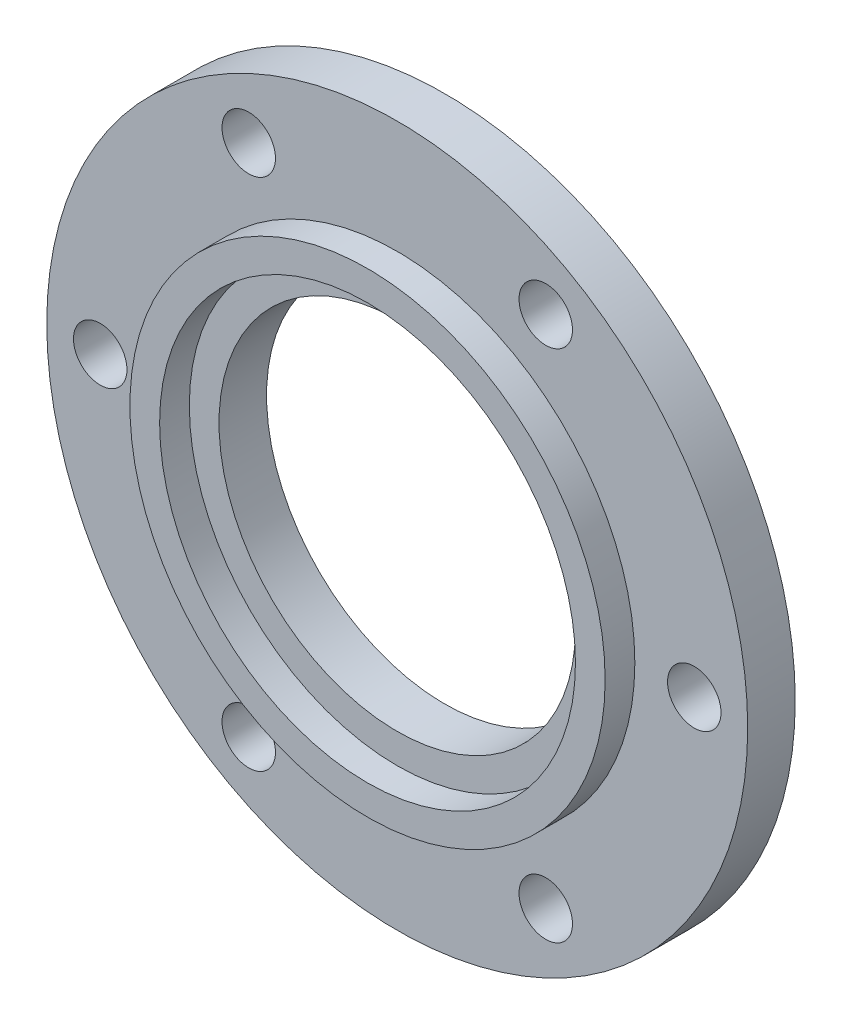
SolidWorks part; units mm, degrees
ref_plane "前视基准面" through (0, 0, 0) normal (0, 0, 1) x (1, 0, 0)
ref_plane "上视基准面" through (0, 0, 0) normal (0, 1, 0) x (1, 0, 0)
ref_plane "右视基准面" through (0, 0, 0) normal (1, 0, 0) x (0, 0, -1)
other "Configuration Table"
sketch "草图1" plane through (0, 0, 0) normal (0, 0, 1) x (1, 0, 0)
  circle A0 centre (0, 0) radius 59
  circle A1 centre (0, 0) radius 30
  dimension "D1" = 118
  dimension "D2" = 60
extrude "凸台-拉伸1" add sketch "草图1" along normal blind 8
sketch "草图2" plane through (0, 0, 8) normal (0, 0, 1) x (1, 0, 0)
  circle A0 centre (0, 0) radius 35
  circle A1 centre (0, 0) radius 40
  dimension "D1" = 70
  dimension "D2" = 80
extrude "凸台-拉伸2" add sketch "草图2" along normal blind 5
sketch "草图3" plane through (0, 0, 8) normal (0, 0, 1) x (1, 0, 0)
  circle A0 centre (0, 0) radius 50 construction
  circle A1 centre (25, 43.3013) radius 4.5
  circle A2 centre (50, 0) radius 4.5
  circle A3 centre (0, 0) radius 50 construction
  circle A4 centre (25, -43.3013) radius 4.5
  circle A5 centre (0, 0) radius 50 construction
  circle A6 centre (-25, -43.3013) radius 4.5
  circle A7 centre (0, 0) radius 50 construction
  circle A8 centre (-50, 0) radius 4.5
  circle A9 centre (0, 0) radius 50 construction
  circle A10 centre (-25, 43.3013) radius 4.5
  circle A11 centre (0, 0) radius 50 construction
  point P8 (25, 43.3013)
  point P25 (0, 0)
  dimension "D1" = 100
  dimension "D2" = 9
  dimension "D3" = 6
extrude "切除-拉伸1" cut sketch "草图3" against normal up to next and the other way through all
